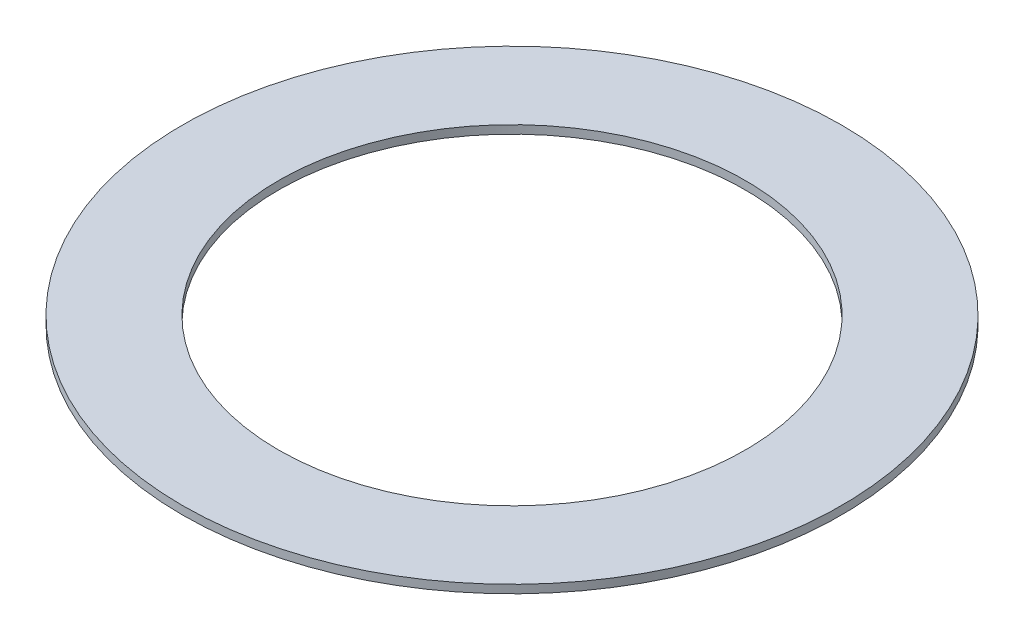
SolidWorks part; units mm, degrees
material "Alloy Steel"
ref_plane "X-Y Datum" through (0, 0, 0) normal (0, 0, 1) x (1, 0, 0)
ref_plane "X-Z Datum" through (0, 0, 0) normal (0, 1, 0) x (1, 0, 0)
ref_plane "Y-Z Datum" through (0, 0, 0) normal (1, 0, 0) x (0, 0, -1)
sketch "Sketch1" plane through (0, 0, 0) normal (0, 1, 0) x (1, 0, 0)
  circle A0 centre (0, 0) radius 8.5
  circle A1 centre (0, 0) radius 12
  dimension "D1" = 17
  dimension "D2" = 24
extrude "Boss-Extrude1" add sketch "Sketch1" along normal blind 0.3
